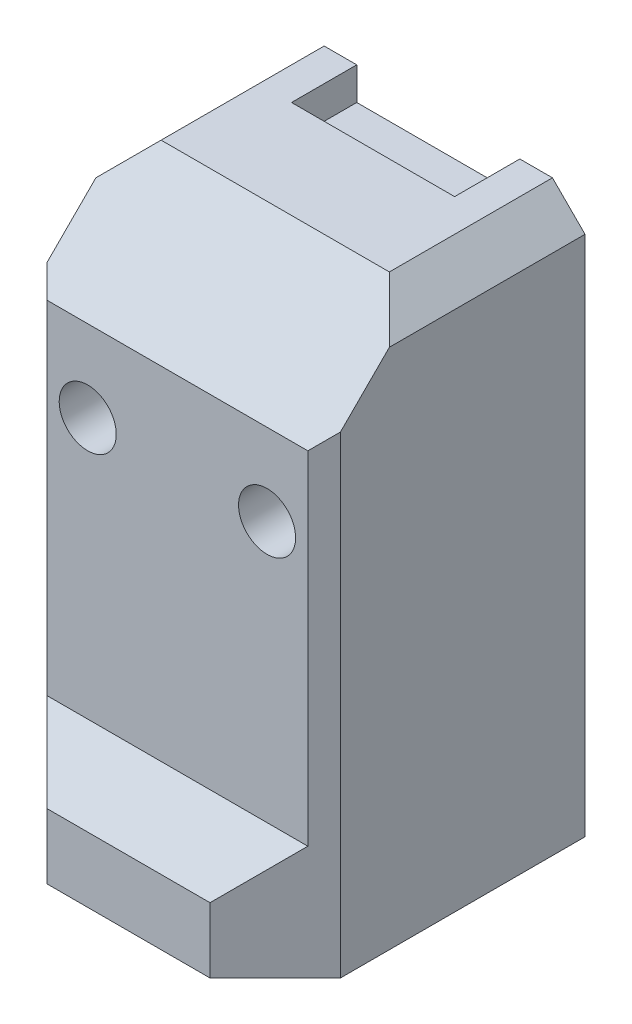
SolidWorks part; units mm, degrees
ref_plane "Front Plane" through (0, 0, 0) normal (0, 0, 1) x (1, 0, 0)
ref_plane "Top Plane" through (0, 0, 0) normal (0, 1, 0) x (1, 0, 0)
ref_plane "Right Plane" through (0, 0, 0) normal (1, 0, 0) x (0, 0, -1)
sketch "Sketch1" plane through (0, 0, 0) normal (0, 0, 1) x (1, 0, 0)
  line L1 (-9, 17) -> (9, 17)
  line L2 (-9, 17) -> (-9, -17)
  line L3 (-9, -17) -> (9, -17)
  line L4 (9, 17) -> (9, -17)
  line L5 (-9, 17) -> (9, -17) construction
  line L6 (-9, -17) -> (9, 17) construction
  circle A0 centre (5.5, 6) radius 1.75
  circle A1 centre (-5.5, 6) radius 1.75
  point P0 (0, 0)
  point P10 (0, 0)
  point P11 (5.7926, 6)
  dimension "D6" = 3.5
  dimension "D1" = 34
  dimension "D2" = 18
  dimension "D3" = 23
  dimension "D4" = 11
  dimension "D5" = 5.5
extrude "Boss-Extrude1" add sketch "Sketch1" along normal blind 19
sketch "Sketch2" plane through (9, 0, 0) normal (1, 0, 0) x (0, 0, -1)
  line L0 (-19, 17) -> (-16, 17)
  line L1 (-19, 17) -> (0, 17) construction
  line L2 (-16, 17) -> (-16, -10)
  line L3 (-16, -10) -> (-19, -13)
  line L4 (-19, -17) -> (-19, 17) construction
  line L5 (-19, -13) -> (-19, 17)
  dimension "D1" = 3
  dimension "D2" = 27
  dimension "D3" = 4
extrude "Cut-Extrude1" cut sketch "Sketch2" against normal blind 18
chamfer "Chamfer1" distance 6 angle 45 1 edges at (0, 17, 16)
chamfer "Chamfer2" distance 2 angle 45 2 edges at (-9, 17, 5) (9, 17, 5)
chamfer "Chamfer3" distance 4 angle 45 2 edges at (-9, -15, 19) (9, -15, 19)
sketch "Sketch3" plane through (0, 17, 0) normal (0, 1, 0) x (1, 0, 0)
  line L0 (7, 0) -> (-7, 0) construction
  line L1 (-5, 0) -> (5, 0)
  line L2 (-5, 0) -> (-5, -4)
  line L3 (-5, -4) -> (5, -4)
  line L4 (5, 0) -> (5, -4)
  point P6 (0, 0)
  dimension "D1" = 10
  dimension "D2" = 5
  dimension "D3" = 4
extrude "Cut-Extrude2" cut sketch "Sketch3" against normal blind 2
